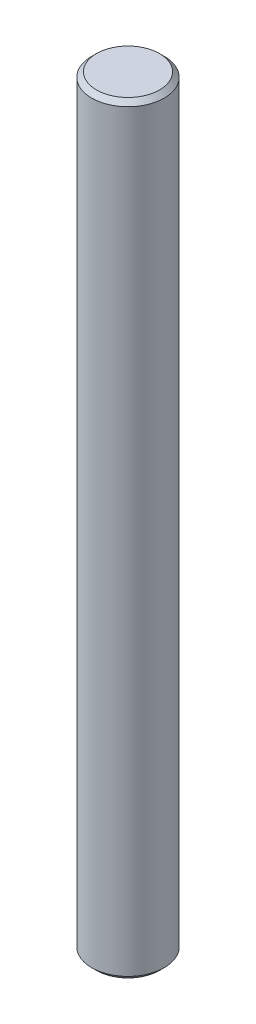
SolidWorks part; units mm, degrees
ref_plane "Front Plane" through (0, 0, 0) normal (0, 0, 1) x (1, 0, 0)
ref_plane "Top Plane" through (0, 0, 0) normal (0, 1, 0) x (1, 0, 0)
ref_plane "Right Plane" through (0, 0, 0) normal (1, 0, 0) x (0, 0, -1)
sketch "Sketch1" plane through (0, 0, 0) normal (0, 1, 0) x (1, 0, 0)
  circle A0 centre (0, 0) radius 3.85
  dimension "D1" = 7.7
extrude "Boss-Extrude1" add sketch "Sketch1" along normal mid plane 81
chamfer "Chamfer1" distance 0.5 angle 45 2 edges at (0, -40.5, 3.85) (0, 40.5, 3.85)
